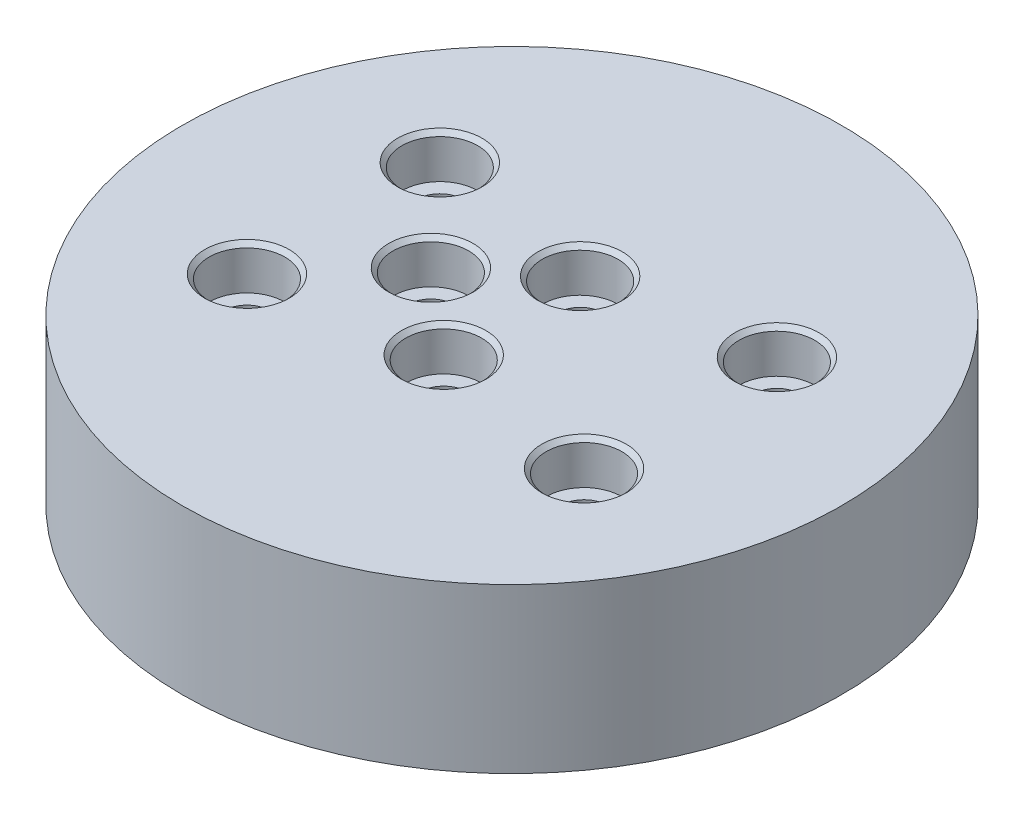
SolidWorks part; units mm, degrees
ref_plane "Front Plane" through (0, 0, 0) normal (0, 0, 1) x (1, 0, 0)
ref_plane "Top Plane" through (0, 0, 0) normal (0, 1, 0) x (1, 0, 0)
ref_plane "Right Plane" through (0, 0, 0) normal (1, 0, 0) x (0, 0, -1)
sketch "Sketch1" plane through (0, 0, 0) normal (0, 1, 0) x (1, 0, 0)
  circle A0 centre (0, 0) radius 48.3128
  point P2 (0, 0)
extrude "Boss-Extrude1" add sketch "Sketch1" along normal blind 24
sketch "Sketch2" plane through (0, 24, 0) normal (0, 1, 0) x (1, 0, 0)
  line L1 (24.7068, -14.1367) -> (-24.7068, -14.1367)
  line L2 (24.7068, -14.1367) -> (24.7068, 14.1367)
  line L3 (24.7068, 14.1367) -> (-24.7068, 14.1367)
  line L4 (-24.7068, -14.1367) -> (-24.7068, 14.1367)
  line L5 (24.7068, -14.1367) -> (-24.7068, 14.1367) construction
  line L6 (24.7068, 14.1367) -> (-24.7068, -14.1367) construction
  point P0 (0, 0)
  point P6 (0, 0)
  point P7 (0, 0)
  point P8 (0, 0)
  point P9 (0, 0)
  point P10 (0, 0)
hole_wizard "CBORE for 1/4 Socket Head Cap Screw1" positions "3DSketch1" profile "Sketch3" counterbore size "1/4" standard "ANSI Inch" end condition up to next
sketch3d "3DSketch1"
  line L0 (0, 24, 10) -> (0, 24, -10) construction
  point P2 (0, 24, 10)
  point P4 (-24.7068, 24, 14.1367)
  point P6 (-24.7068, 24, -14.1367)
  point P8 (24.7068, 24, -14.1367)
  point P10 (0, 24, -10)
  point P12 (24.7068, 24, 14.1367)
  point P31 (-12, 24, -0.1211)
  point P34 (0, 0, 0)
  point P35 (-7.9961, 24, 29.9668)
  point P36 (-12.4626, 24, -0.1211)
  dimension "D1" = 20
  dimension "D2" = 12
sketch "Sketch3" plane through (0, 24, 10) normal (1, 0, 0) x (0, 0, 1)
  line L0 (0, 0) -> (0, 24)
  line L1 (0, 24) -> (3.3782, 24)
  line L3 (3.3782, 24) -> (3.3782, 6.35)
  line L4 (5.5562, 6.35) -> (3.3782, 6.35)
  line L5 (5.5562, 6.35) -> (5.5562, 0.635)
  line L6 (5.5562, 0.635) -> (6.1913, 0)
  line L7 (6.1913, 0) -> (0, 0)
  line L8 (-5.5562, 0.635) -> (-6.1913, 0) construction
  line L11 (0, -6.35) -> (0, 107.95) construction
  dimension "Thru Hole Dia." = 6.7564
  dimension "Thru Hole Depth" = 24
  dimension "C'Bore Dia." = 11.1125
  dimension "C'Bore Depth" = 6.35
  dimension "Near C'Sink Dia." = 12.3825
  dimension "Near C'Sink Angle" = 90
